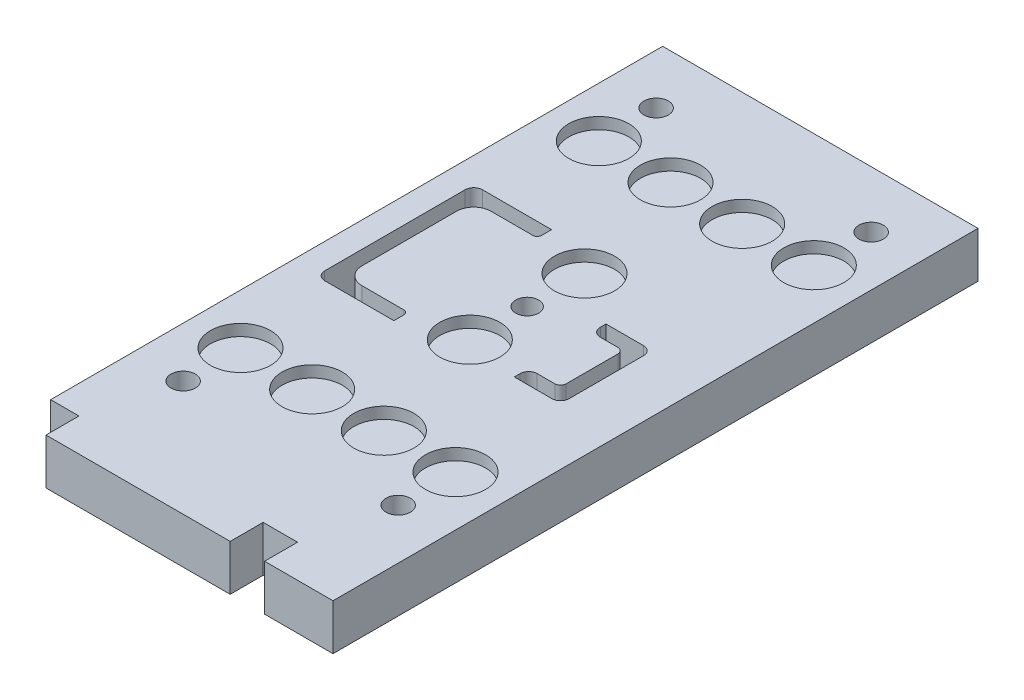
SolidWorks part; units mm, degrees
material "Plain Carbon Steel"
ref_plane "Front Plane" through (0, 0, 0) normal (0, 0, 1) x (1, 0, 0)
ref_plane "Top Plane" through (0, 0, 0) normal (0, 1, 0) x (1, 0, 0)
ref_plane "Right Plane" through (0, 0, 0) normal (1, 0, 0) x (0, 0, -1)
sketch "Sketch1" plane through (0, 0, 0) normal (0, 1, 0) x (1, 0, 0)
  line L1 (-55, -112.5) -> (55, -112.5)
  line L2 (-55, -112.5) -> (-55, 112.5)
  line L3 (-55, 112.5) -> (55, 112.5)
  line L4 (55, -112.5) -> (55, 112.5)
  line L5 (-55, -112.5) -> (55, 112.5) construction
  line L6 (-55, 112.5) -> (55, -112.5) construction
  point P0 (0, 0)
  dimension "D1" = 110
  dimension "D2" = 225
extrude "Boss-Extrude1" add sketch "Sketch1" against normal blind 16
sketch "Sketch2" plane through (0, 0, 0) normal (0, 1, 0) x (1, 0, 0)
  line L0 (-19, 37.73) -> (-19, 34.23) construction
  line L1 (-43.12, 37.73) -> (-19, 37.73) construction
  line L2 (-46.12, 34.73) -> (-46.12, -14.27) construction
  line L3 (-43.12, -17.27) -> (-19, -17.27) construction
  line L4 (-19, -17.27) -> (-19, -13.77) construction
  line L5 (-35.12, -12.27) -> (-20.5, -12.27) construction
  line L6 (-41.12, 26.73) -> (-41.12, -6.27) construction
  line L7 (-20.5, 32.73) -> (-35.12, 32.73) construction
  line L8 (-19, 37.73) -> (-19, 34.23)
  line L9 (-43.12, 37.73) -> (-19, 37.73)
  line L10 (-46.12, 34.73) -> (-46.12, -14.27)
  line L11 (-43.12, -17.27) -> (-19, -17.27)
  line L12 (-19, -17.27) -> (-19, -13.77)
  line L13 (-35.12, -12.27) -> (-20.5, -12.27)
  line L14 (-41.12, 26.73) -> (-41.12, -6.27)
  line L15 (-20.5, 32.73) -> (-35.12, 32.73)
  arc A0 (-20.5, 32.73) -> (-19, 34.23) centre (-20.5, 34.23) ccw construction
  arc A1 (-43.12, 37.73) -> (-46.12, 34.73) centre (-43.12, 34.73) ccw construction
  arc A2 (-46.12, -14.27) -> (-43.12, -17.27) centre (-43.12, -14.27) ccw construction
  arc A3 (-19, -13.77) -> (-20.5, -12.27) centre (-20.5, -13.77) ccw construction
  arc A4 (-41.12, -6.27) -> (-35.12, -12.27) centre (-35.12, -6.27) ccw construction
  arc A5 (-35.12, 32.73) -> (-41.12, 26.73) centre (-35.12, 26.73) ccw construction
  arc A6 (-20.5, 32.73) -> (-19, 34.23) centre (-20.5, 34.23) ccw
  arc A7 (-43.12, 37.73) -> (-46.12, 34.73) centre (-43.12, 34.73) ccw
  arc A8 (-46.12, -14.27) -> (-43.12, -17.27) centre (-43.12, -14.27) ccw
  arc A9 (-19, -13.77) -> (-20.5, -12.27) centre (-20.5, -13.77) ccw
  arc A10 (-41.12, -6.27) -> (-35.12, -12.27) centre (-35.12, -6.27) ccw
  arc A11 (-35.12, 32.73) -> (-41.12, 26.73) centre (-35.12, 26.73) ccw
extrude "Cut-Extrude1" cut sketch "Sketch2" against normal up to next
sketch "Sketch3" plane through (0, 0, 0) normal (0, 1, 0) x (1, 0, 0)
  line L0 (19, 18.73) -> (32.13, 18.73) construction
  line L1 (19, 18.73) -> (19, 16.73) construction
  line L2 (28.13, 13.73) -> (22, 13.73) construction
  line L3 (30.13, -6.27) -> (30.13, 11.73) construction
  line L4 (22, -8.27) -> (28.13, -8.27) construction
  line L5 (19, -13.27) -> (19, -11.27) construction
  line L6 (32.13, -13.27) -> (19, -13.27) construction
  line L7 (35.13, 15.73) -> (35.13, -10.27) construction
  line L8 (19, 18.73) -> (32.13, 18.73)
  line L9 (19, 18.73) -> (19, 16.73)
  line L10 (28.13, 13.73) -> (22, 13.73)
  line L11 (30.13, -6.27) -> (30.13, 11.73)
  line L12 (22, -8.27) -> (28.13, -8.27)
  line L13 (19, -13.27) -> (19, -11.27)
  line L14 (32.13, -13.27) -> (19, -13.27)
  line L15 (35.13, 15.73) -> (35.13, -10.27)
  arc A0 (35.13, 15.73) -> (32.13, 18.73) centre (32.13, 15.73) ccw construction
  arc A1 (19, 16.73) -> (22, 13.73) centre (22, 16.73) ccw construction
  arc A2 (30.13, 11.73) -> (28.13, 13.73) centre (28.13, 11.73) ccw construction
  arc A3 (28.13, -8.27) -> (30.13, -6.27) centre (28.13, -6.27) ccw construction
  arc A4 (22, -8.27) -> (19, -11.27) centre (22, -11.27) ccw construction
  arc A5 (32.13, -13.27) -> (35.13, -10.27) centre (32.13, -10.27) ccw construction
  arc A6 (35.13, 15.73) -> (32.13, 18.73) centre (32.13, 15.73) ccw
  arc A7 (19, 16.73) -> (22, 13.73) centre (22, 16.73) ccw
  arc A8 (30.13, 11.73) -> (28.13, 13.73) centre (28.13, 11.73) ccw
  arc A9 (28.13, -8.27) -> (30.13, -6.27) centre (28.13, -6.27) ccw
  arc A10 (22, -8.27) -> (19, -11.27) centre (22, -11.27) ccw
  arc A11 (32.13, -13.27) -> (35.13, -10.27) centre (32.13, -10.27) ccw
extrude "Cut-Extrude2" cut sketch "Sketch3" against normal up to next
sketch "Sketch4" plane through (0, -16, 0) normal (0, -1, 0) x (1, 0, 0)
  circle A0 centre (0, 100) radius 8.5
  circle A1 centre (0, -100) radius 8.5
  dimension "D1" = 17
extrude "Cut-Extrude3" cut sketch "Sketch4" against normal blind 5
sketch "Sketch5" plane through (0, 0, 0) normal (0, 1, 0) x (1, 0, 0)
  line L2 (-55, 112.5) -> (-55, -112.5) construction
  line L5 (-19, 37.73) -> (-43.12, 37.73) construction
  line L6 (-41.12, 10.23) -> (30.13, 10.23) construction
  line L7 (-41.12, -6.27) -> (-41.12, 26.73) construction
  line L9 (30.13, 11.73) -> (30.13, -6.27) construction
  circle A0 centre (-37.5, 72.73) radius 10.5
  circle A1 centre (-12.5, 72.73) radius 10.5
  circle A2 centre (12.5, 72.73) radius 10.5
  circle A3 centre (37.5, 72.73) radius 10.5
  circle A4 centre (37.5, -52.27) radius 10.5
  circle A5 centre (12.5, -52.27) radius 10.5
  circle A6 centre (-12.5, -52.27) radius 10.5
  circle A7 centre (-37.5, -52.27) radius 10.5
  circle A8 centre (0, 30.23) radius 10.5
  circle A9 centre (0, -9.77) radius 10.5
  point P30 (0, 0)
  dimension "D1" = 21
  dimension "D2" = 17.5
  dimension "D3" = 35
  dimension "D5" = 25
  dimension "D6" = 20
  dimension "D7" = 20
  dimension "D4" = 4
extrude "Cut-Extrude4" cut sketch "Sketch5" against normal blind 4
sketch "Sketch6" plane through (0, 0, 0) normal (0, 1, 0) x (1, 0, 0)
  line L0 (-55, -112.5) -> (55, -112.5) construction
  line L1 (31.13, -112.5) -> (19.13, -112.5)
  line L2 (31.13, -112.5) -> (31.13, -101)
  line L3 (31.13, -101) -> (19.13, -101)
  line L4 (19.13, -112.5) -> (19.13, -101)
  line L5 (20.63, -102) -> (29.63, -102) construction
  line L6 (-45.12, -112.5) -> (-57.12, -112.5)
  line L7 (-45.12, -112.5) -> (-45.12, -101)
  line L8 (-45.12, -101) -> (-57.12, -101)
  line L9 (-57.12, -112.5) -> (-57.12, -101)
  line L10 (30.13, -102.5) -> (30.13, -115) construction
  line L11 (20.13, -115) -> (20.13, -102.5) construction
  line L12 (-56.12, -115) -> (-56.12, -102.5) construction
  line L13 (-46.12, -102.5) -> (-46.12, -115) construction
  line L14 (-55.62, -102) -> (-46.62, -102) construction
  dimension "D1" = 1
  dimension "D2" = 1
  dimension "D3" = 1
  dimension "D4" = 1
  dimension "D5" = 1
  dimension "D6" = 1
extrude "Cut-Extrude5" cut sketch "Sketch6" against normal up to next
hole_wizard "M10 Tapped Hole1" positions "Sketch9" profile "Sketch8" tap size "M10" standard "ISO" end condition through all
sketch "Sketch9" plane through (0, 0, 0) normal (0, 1, 0) x (1, 0, 0)
  line L2 (-37.5, 72.73) -> (-37.5, 92.73) construction
  line L4 (37.5, 72.73) -> (37.5, 92.73) construction
  circle A1 centre (-37.5, 72.73) radius 10.5 construction
  circle A2 centre (-37.5, -52.27) radius 10.5 construction
  point P0 (-37.5, -72.27)
  point P2 (37.5, -72.27)
  point P4 (37.5, 92.73)
  point P6 (-37.5, 92.73)
  point P30 (0, 0)
  point P31 (0, 0)
  point P32 (0, 0)
  point P33 (-37.5, -80.3238)
  dimension "D1" = 20
  dimension "D2" = 20
sketch "Sketch8" plane through (-37.5, 0, 72.27) normal (1, 0, 0) x (0, 0, 1)
  line L0 (0, 0) -> (0, 16)
  line L1 (0, 16) -> (4.25, 16)
  line L2 (4.25, 16) -> (4.25, 0)
  line L5 (4.25, 0) -> (0, 0)
  line L11 (0, -6.35) -> (0, 107.95) construction
  dimension "Thru Tap Drill Dia." = 8.5
  dimension "Thru Tap Drill Depth" = 16
cosmetic thread "Hole Thread1" parameters "D2"=10
cosmetic thread "Hole Thread2" parameters "D2"=10
cosmetic thread "Hole Thread3" parameters "D2"=10
cosmetic thread "Hole Thread4" parameters "D2"=10
sketch "Sketch10" plane through (0, 0, 0) normal (0, 1, 0) x (1, 0, 0)
  circle A0 centre (0, 10.23) radius 5 construction
  circle A1 centre (0, 10.23) radius 5 construction
  circle A2 centre (0, 10.23) radius 4
  dimension "D1" = 8
extrude "Cut-Extrude6" cut sketch "Sketch10" against normal up to next
